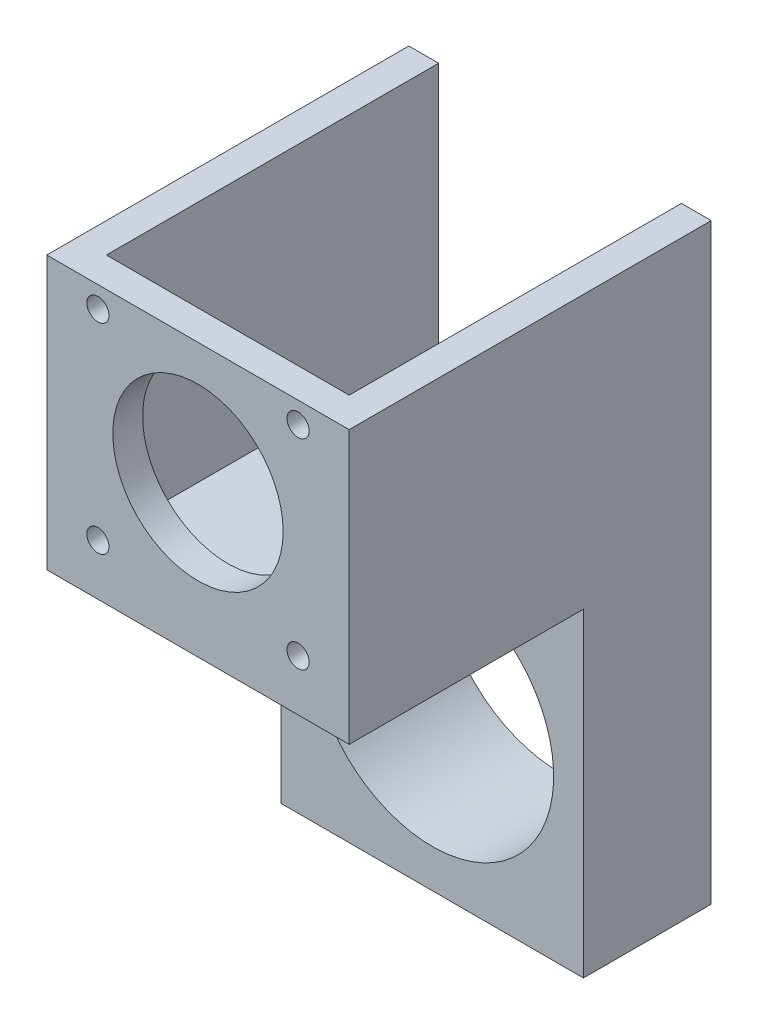
SolidWorks part; units mm, degrees
ref_plane "Front Plane" through (0, 0, 0) normal (0, 0, 1) x (1, 0, 0)
ref_plane "Top Plane" through (0, 0, 0) normal (0, 1, 0) x (1, 0, 0)
ref_plane "Right Plane" through (0, 0, 0) normal (1, 0, 0) x (0, 0, -1)
sketch "Sketch1" plane through (0, 0, 0) normal (0, 0, 1) x (1, 0, 0)
  line L0 (-81.2971, 62) -> (-81.2971, 25.5) construction
  line L1 (-78.2971, 8) -> (-41.7971, 8) construction
  line L2 (-24.2971, 11) -> (-24.2971, 47.5) construction
  line L3 (-27.2971, 65) -> (-63.7971, 65) construction
  line L4 (-81.2971, 62) -> (-81.2971, 25.5)
  line L5 (-78.2971, 8) -> (-41.7971, 8)
  line L6 (-24.2971, 11) -> (-24.2971, 47.5)
  line L7 (-27.2971, 65) -> (-63.7971, 65)
  line L8 (-63.7971, 65) -> (-81.2971, 65)
  line L9 (-81.2971, 65) -> (-81.2971, 62)
  line L10 (-81.2971, 25.5) -> (-81.2971, 8)
  line L11 (-81.2971, 8) -> (-78.2971, 8)
  line L12 (-41.7971, 8) -> (-24.2971, 8)
  line L13 (-24.2971, 8) -> (-24.2971, 11)
  line L14 (-24.2971, 47.5) -> (-24.2971, 65)
  line L15 (-24.2971, 65) -> (-27.2971, 65)
  circle A0 centre (-76.2971, 13) radius 2.6 construction
  circle A1 centre (-29.2971, 13) radius 2.6 construction
  circle A2 centre (-29.2971, 60) radius 2.6 construction
  circle A3 centre (-76.2971, 60) radius 2.6 construction
  circle A4 centre (-76.2971, 13) radius 2.6
  circle A5 centre (-29.2971, 13) radius 2.6
  circle A6 centre (-29.2971, 60) radius 2.6
  circle A7 centre (-76.2971, 60) radius 2.6
extrude "Boss-Extrude1" add sketch "Sketch1" along normal blind 7
sketch "Sketch3" plane through (0, 0, 7) normal (0, 0, 1) x (1, 0, 0)
  circle A3 centre (-52.7971, 36.5) radius 20
extrude "Cut-Extrude1" cut sketch "Sketch3" against normal through all
sketch "Sketch4" plane through (0, 0, 7) normal (0, 0, 1) x (1, 0, 0)
  line L0 (-81.2971, 8) -> (-24.2971, 8) construction
  line L1 (-24.2971, 8) -> (-24.2971, 65) construction
  line L2 (-24.2971, 65) -> (-81.2971, 65) construction
  line L3 (-81.2971, 65) -> (-81.2971, 8) construction
  line L4 (-81.2971, 8) -> (-24.2971, 8)
  line L5 (-24.2971, 8) -> (-24.2971, 65)
  line L6 (-24.2971, 65) -> (-81.2971, 65)
  line L7 (-81.2971, 65) -> (-81.2971, 8)
  line L8 (-88.2971, 65) -> (-88.2971, 1)
  line L9 (-88.2971, 1) -> (-17.2971, 1)
  line L10 (-17.2971, 1) -> (-17.2971, 65)
  line L12 (-81.2971, 65) -> (-88.2971, 65)
  line L13 (-24.2971, 65) -> (-17.2971, 65)
  line L15 (-88.2971, 72) -> (-88.2971, 1) construction
  line L16 (-17.2971, 72) -> (-88.2971, 72) construction
  line L17 (-17.2971, 1) -> (-17.2971, 72) construction
  line M5 (-81.2971, 65) -> (-81.2971, 8)
  line M6 (-81.2971, 8) -> (-24.2971, 8)
  line M7 (-24.2971, 8) -> (-24.2971, 65)
  dimension "D1" = 7
extrude "Boss-Extrude2" add sketch "Sketch4" against normal blind 75 contours L13 L12 L8 L9 L10 M7 M6 M5
sketch "Sketch5" plane through (0, 0, -68) normal (0, 0, -1) x (-1, 0, 0)
  line L0 (88.2971, 1) -> (88.2971, -74)
  line L2 (17.2971, -74) -> (17.2971, 1)
  line L4 (52.7971, -74) -> (88.2971, -74)
  line L5 (52.7971, -74) -> (17.2971, -74)
  line L8 (24.2971, 65) -> (17.2971, 65)
  line L9 (17.2971, 65) -> (17.2971, 1)
  line L10 (17.2971, 1) -> (88.2971, 1)
  line L11 (88.2971, 1) -> (88.2971, 65)
  line L12 (88.2971, 65) -> (81.2971, 65)
  line L13 (81.2971, 65) -> (81.2971, 8)
  line L14 (81.2971, 8) -> (24.2971, 8)
  line L15 (24.2971, 8) -> (24.2971, 65)
  line L16 (24.2971, 65) -> (17.2971, 65)
  line L17 (17.2971, 65) -> (17.2971, 1)
  line L19 (88.2971, 1) -> (88.2971, 65)
  line L20 (88.2971, 65) -> (81.2971, 65)
  line L21 (81.2971, 65) -> (81.2971, 8)
  line L22 (81.2971, 8) -> (24.2971, 8)
  line L23 (24.2971, 8) -> (24.2971, 65)
  circle A0 centre (52.7971, -36.5) radius 28.5
  dimension "D1" = 0
extrude "Boss-Extrude3" add sketch "Sketch5" along normal blind 10 and the other way blind 20
